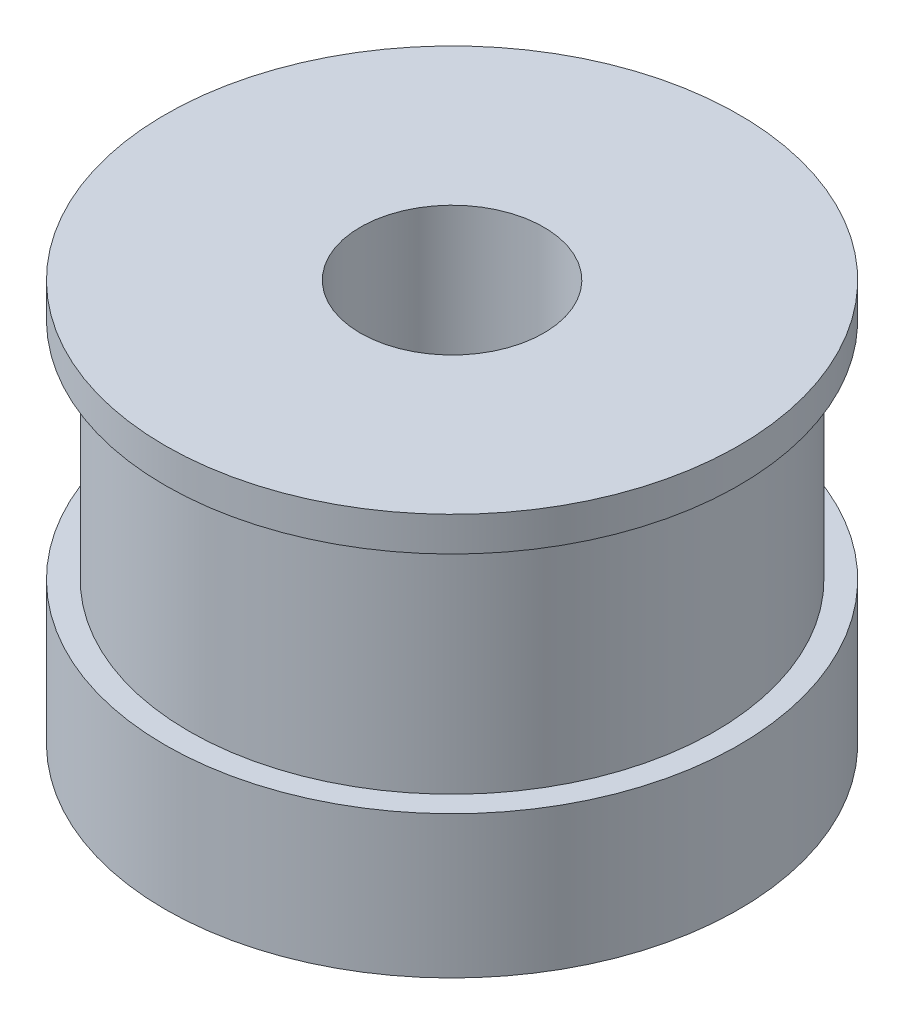
SolidWorks part; units mm, degrees
ref_plane "Front" through (0, 0, 0) normal (0, 0, 1) x (1, 0, 0)
ref_plane "Top" through (0, 0, 0) normal (0, 1, 0) x (1, 0, 0)
ref_plane "Right" through (0, 0, 0) normal (1, 0, 0) x (0, 0, -1)
sketch "Sketch1" plane through (0, 0, 0) normal (1, 0, 0) x (0, 0, -1)
  line L0 (0, 10.3155) -> (0, -12.6924) construction
  line L1 (-13.3377, 0) -> (15.1571, 0) construction
  line L3 (12.5, 7.25) -> (12.5, 8.75)
  line L4 (12.5, 8.75) -> (4, 8.75)
  line L5 (11.46, 7.25) -> (12.5, 7.25)
  line L6 (4, 8.75) -> (4, -8.75)
  line L9 (12.5, -8.75) -> (4, -8.75)
  line L10 (11.46, 7.25) -> (11.46, -2.55)
  line L11 (11.46, -2.55) -> (12.5, -2.55)
  line L13 (12.5, -2.55) -> (12.5, -8.75)
  point P11 (11.46, 0)
  point P15 (4, 0)
  dimension "D1" = 1.5
  dimension "D2" = 8.75
  dimension "D3" = 12.5
  dimension "D4" = 1.04
  dimension "D5" = 9.8
  dimension "2" = 4
revolve "Revolve1" add sketch "Sketch1" angle 360 about L0
sketch "Sketch2" plane through (0, 8.75, 0) normal (0, 1, 0) x (1, 0, 0)
  circle A0 centre (0, 0) radius 5.1
  circle A3 centre (8, 0) radius 1.75
  circle A5 centre (0, -8) radius 1.75
  circle A6 centre (-8, 0) radius 1.75
  circle A7 centre (0, 8) radius 1.75
  point P22 (0, 0)
  dimension "D1" = 4
